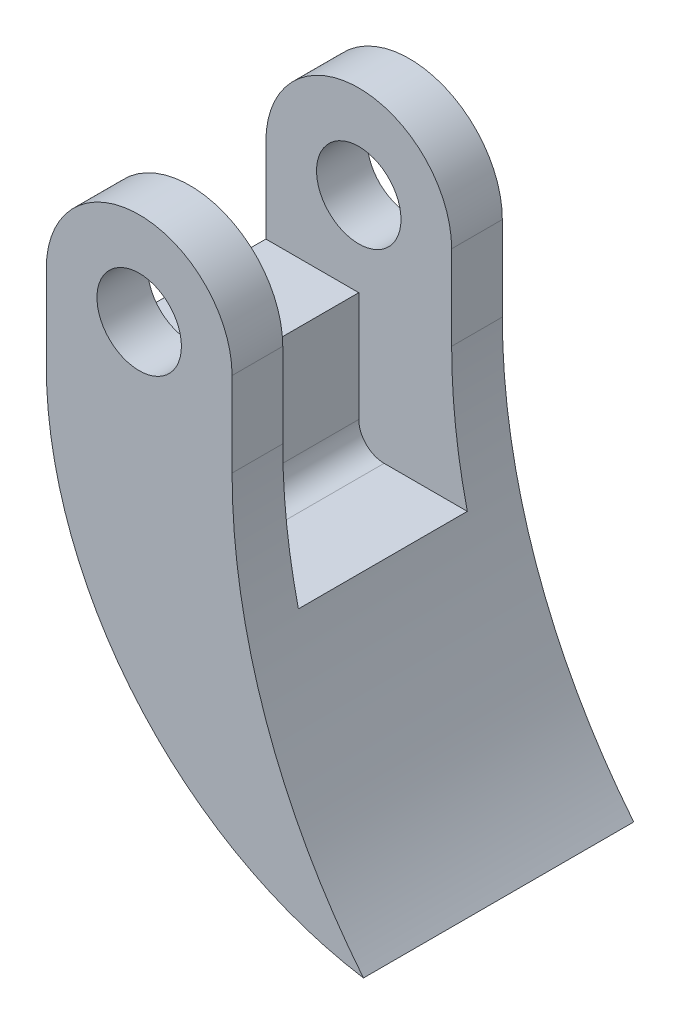
SolidWorks part; units mm, degrees
ref_plane "前视基准面" through (0, 0, 0) normal (0, 0, 1) x (1, 0, 0)
ref_plane "上视基准面" through (0, 0, 0) normal (0, 1, 0) x (1, 0, 0)
ref_plane "右视基准面" through (0, 0, 0) normal (1, 0, 0) x (0, 0, -1)
sketch "草图1" plane through (0, 0, 0) normal (0, 0, 1) x (1, 0, 0)
  line L0 (1.3385, 67.0602) -> (1.3385, 62.0602) construction
  line L2 (-4.1615, 67.0602) -> (-4.1615, 62.0602)
  line L3 (6.8385, 67.0602) -> (6.8385, 62.0602)
  circle A1 centre (1.3385, 67.0602) radius 3 construction
  arc A2 (-4.1615, 67.0602) -> (6.8385, 67.0602) centre (1.3385, 67.0602) cw
  arc A3 (6.8385, 62.0602) -> (14.6172, 40.0602) centre (41.8385, 62.0602) ccw
  arc A4 (-4.1615, 62.0602) -> (14.6172, 40.0602) centre (18.1148, 62.0602) ccw
  circle A5 centre (19.0893, 43.6745) radius 5.75 construction
  dimension "D1" = 5.5
  dimension "D2" = 11.5
  dimension "D3" = 35
extrude "凸台-拉伸1" add sketch "草图1" along normal blind 16
sketch "草图2" plane through (0, 0, 16) normal (0, 0, 1) x (1, 0, 0)
  circle A2 centre (1.3385, 67.0602) radius 2.5
  dimension "D1" = 5
extrude "切除-拉伸1" cut sketch "草图2" against normal through all
sketch "草图3" plane through (6.8385, 0, 0) normal (1, 0, 0) x (0, 0, -1)
  line L2 (-16, 62.0602) -> (0, 62.0602) construction
  line L3 (-8, 64.0602) -> (-8, 72.5602) construction
  line L4 (-16, 67.0602) -> (0, 67.0602) construction
  line L5 (-16, 67.0602) -> (0, 67.0602) construction
  line L6 (-16, 64.0602) -> (0, 64.0602) construction
  line L7 (-16, 64.0602) -> (0, 64.0602) construction
  line L8 (0, 72.5602) -> (-16, 72.5602) construction
  line L9 (-13, 72.5602) -> (-13, 62.0602)
  line L10 (-13, 62.0602) -> (-3, 62.0602)
  line L11 (-3, 62.0602) -> (-3, 72.5602)
  line L12 (-3, 72.5602) -> (-13, 72.5602)
  dimension "D1" = 2
  dimension "D2" = 10
  dimension "D3" = 2
extrude "切除-拉伸2" cut sketch "草图3" against normal blind 16
sketch "草图4" plane through (0, 62.0602, 0) normal (0, 1, 0) x (1, 0, 0)
  line L0 (4.3385, 0) -> (4.3385, 4) construction
  line L1 (-1.6615, 4) -> (-1.6615, 0) construction
  line L2 (4.3385, -22) -> (4.3385, 4) construction
  line L3 (-1.6615, 4) -> (-1.6615, -22) construction
  line L5 (-13.1502, -22) -> (134.6932, -22) construction
  line L6 (1.3385, -13) -> (1.3385, -3)
  line L7 (6.8385, -13) -> (-4.1615, -13) construction
  line L8 (-4.1615, -3) -> (6.8385, -3) construction
  line L9 (1.3385, -3) -> (8.3385, -3)
  line L11 (8.3385, -3) -> (8.3385, -13)
  line L12 (8.3385, -13) -> (1.3385, -13)
  dimension "D1" = 7
extrude "切除-拉伸3" cut sketch "草图4" against normal blind 8
fillet "圆角1" radius 1.5 1 edges at (1.3385, 54.0602, 8)
